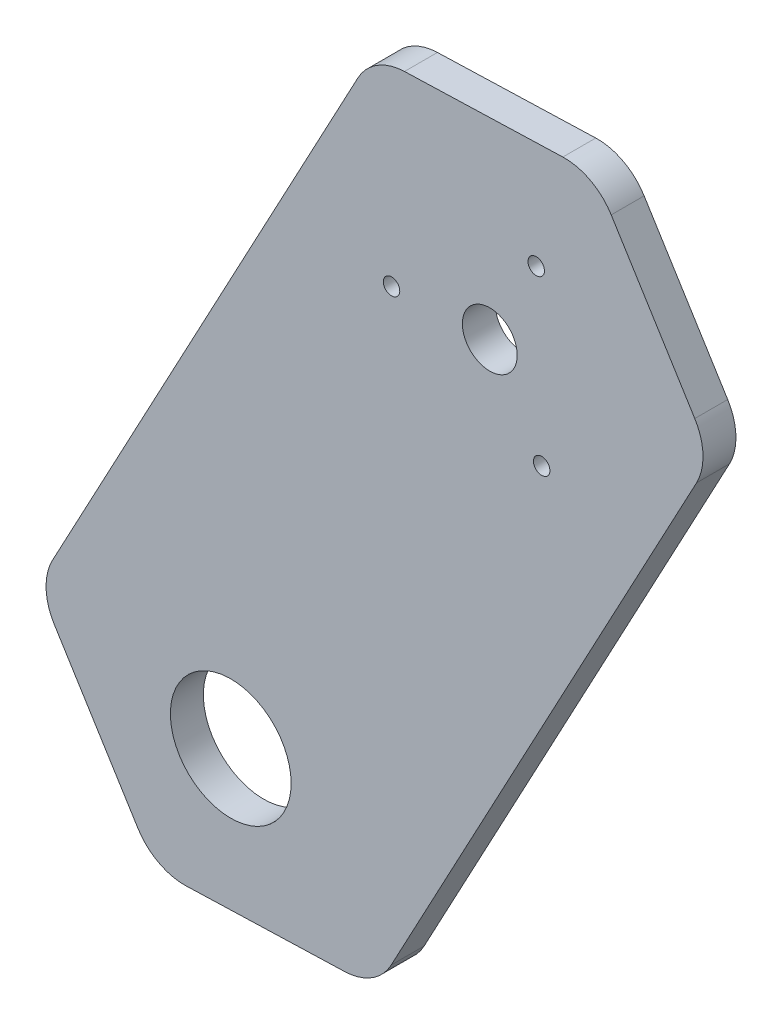
SolidWorks part; units mm, degrees
ref_plane "Front Plane" through (0, 0, 0) normal (0, 0, 1) x (1, 0, 0)
ref_plane "Top Plane" through (0, 0, 0) normal (0, 1, 0) x (1, 0, 0)
ref_plane "Right Plane" through (0, 0, 0) normal (1, 0, 0) x (0, 0, -1)
sketch "Sketch1" plane through (0, 0, 0) normal (0, 0, 1) x (1, 0, 0)
  line L6 (-15.825, 248.9866) -> (-31.0514, 273.5119)
  line L7 (21.8435, 245.19) -> (-7.0092, 244.2663)
  line L8 (85.9766, 354.3744) -> (30.3393, 250.4646)
  line L9 (70.4302, 388.8946) -> (85.6566, 364.3693)
  line L10 (32.7617, 392.6912) -> (61.6144, 393.6149)
  line L11 (-31.3714, 283.5068) -> (24.2659, 387.4166)
  circle A11 centre (56.7655, 373.9664) radius 1.5
  circle A12 centre (57.7585, 342.9489) radius 1.5
  circle A13 centre (30.4001, 357.5976) radius 1.5
  circle A14 centre (48.308, 358.171) radius 5
  circle A15 centre (1.1048, 270.0128) radius 11
  arc A16 (-31.3714, 283.5068) -> (-31.0514, 273.5119) centre (-22.5555, 278.7865) ccw
  arc A17 (-15.825, 248.9866) -> (-7.0092, 244.2663) centre (-7.3292, 254.2612) ccw
  arc A18 (21.8435, 245.19) -> (30.3393, 250.4646) centre (21.5235, 255.1849) ccw
  arc A19 (85.9766, 354.3744) -> (85.6566, 364.3693) centre (77.1608, 359.0947) ccw
  arc A20 (70.4302, 388.8946) -> (61.6144, 393.6149) centre (61.9344, 383.62) ccw
  arc A21 (32.7617, 392.6912) -> (24.2659, 387.4166) centre (33.0817, 382.6963) ccw
  point P1 (0, 0)
  point P3 (87.1556, 359.4147)
  point P5 (0, 0)
  point P9 (-2.4922, 273.831)
  dimension "D1" = 10
  dimension "D11" = 22
  dimension "D21" = 3
  dimension "D22" = 10
  dimension "D2" = 60
  dimension "D3" = 60
  dimension "D4" = 60
  dimension "D5" = 60
  dimension "D6" = 60
  dimension "D7" = 60
  dimension "D8" = 117.8675
  dimension "D9" = 28.8675
  dimension "D10" = 28.8675
  dimension "D12" = 245.19
  dimension "D13" = 21.8435
  dimension "D14" = 244.3655
  dimension "D15" = 25.4737
  dimension "D16" = 25.4737
  dimension "D17" = 100
  dimension "D18" = 31.0333
  dimension "D19" = 31.0333
  dimension "D20" = 31.0333
  dimension "D23" = 17.9171
  dimension "D24" = 19.4833
  dimension "D25" = 19.4833
  dimension "D26" = 19.4833
extrude "Boss-Extrude1" add sketch "Sketch1" along normal blind 6 separate body
